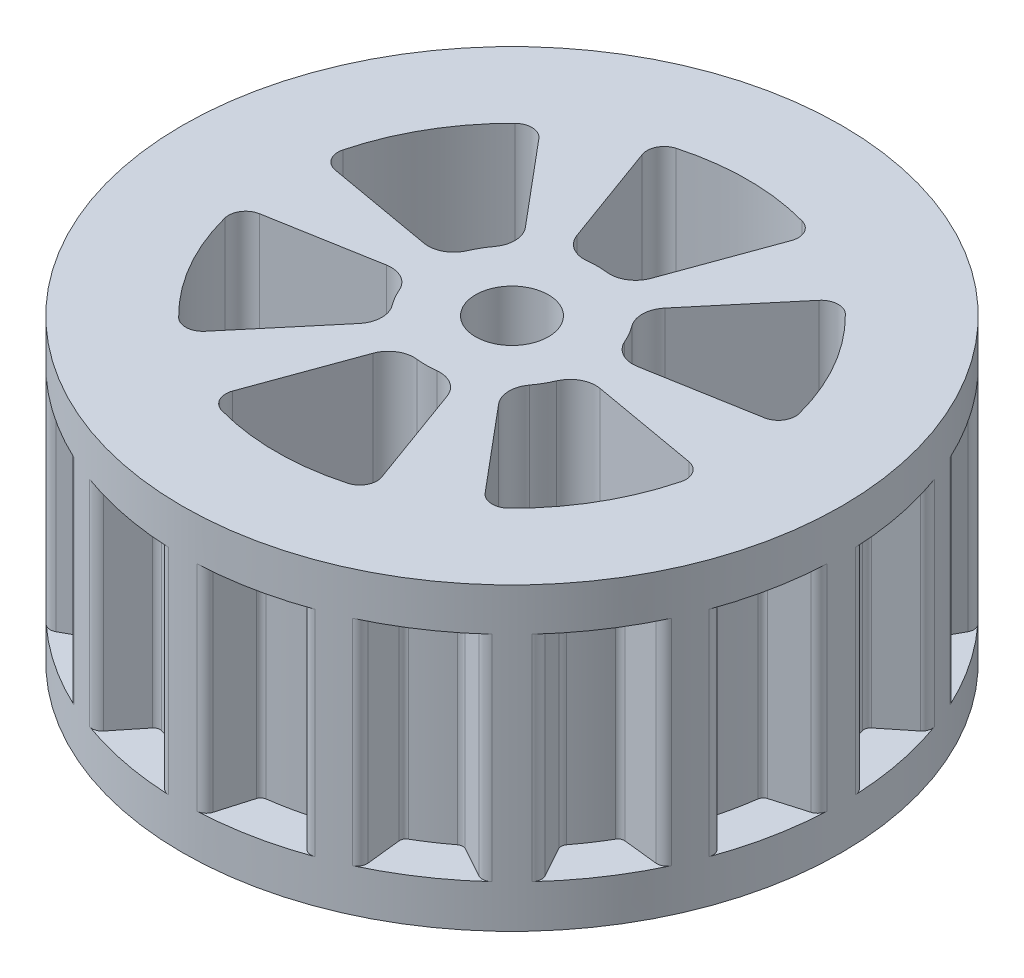
SolidWorks part; units mm, degrees
ref_plane "前视基准面" through (0, 0, 0) normal (0, 0, 1) x (1, 0, 0)
ref_plane "上视基准面" through (0, 0, 0) normal (0, 1, 0) x (1, 0, 0)
ref_plane "右视基准面" through (0, 0, 0) normal (1, 0, 0) x (0, 0, -1)
sketch "草图1" plane through (0, 0, 0) normal (0, 1, 0) x (1, 0, 0)
  circle A0 centre (0, 0) radius 76.925
extrude "凸台-拉伸1" add sketch "草图1" along normal blind 10
ref_plane "基准面1" through (0, 10, 0) normal (0, 1, 0) x (1, 0, 0)
sketch "草图2" plane through (0, 10, 0) normal (0, 1, 0) x (1, 0, 0)
  line L0 (0, 47.7566) -> (0, -19.898) construction
  line L1 (-34.7968, 0) -> (37.1562, 0) construction
  line L2 (0, 0) -> (6.2332, 95.8691) construction
  line L3 (4.9909, 76.7629) -> (8.95, 63.2066) construction
  line L4 (0, 0) -> (18.3427, 92.2148) construction
  line L5 (5.4476, 75.1994) -> (7.729, 67.3874)
  line L6 (-5.4476, 75.1994) -> (-7.729, 67.3874)
  line L7 (23.7447, 71.5599) -> (18.6474, 65.2156)
  line L8 (33.8105, 67.3905) -> (32.9287, 59.3001)
  line L9 (49.322, 57.026) -> (42.1849, 53.1153)
  line L10 (57.026, 49.322) -> (53.1153, 42.1849)
  line L11 (67.3905, 33.8105) -> (59.3001, 32.9287)
  line L12 (71.5599, 23.7447) -> (65.2156, 18.6474)
  line L13 (75.1994, 5.4476) -> (67.3874, 7.729)
  line L14 (75.1994, -5.4476) -> (67.3874, -7.729)
  line L15 (71.5599, -23.7447) -> (65.2156, -18.6474)
  line L16 (67.3905, -33.8105) -> (59.3001, -32.9287)
  line L17 (57.026, -49.322) -> (53.1153, -42.1849)
  line L18 (49.322, -57.026) -> (42.1849, -53.1153)
  line L19 (33.8105, -67.3905) -> (32.9287, -59.3001)
  line L20 (23.7447, -71.5599) -> (18.6474, -65.2156)
  line L21 (5.4476, -75.1994) -> (7.729, -67.3874)
  line L22 (-5.4476, -75.1994) -> (-7.729, -67.3874)
  line L23 (-23.7447, -71.5599) -> (-18.6474, -65.2156)
  line L24 (-33.8105, -67.3905) -> (-32.9287, -59.3001)
  line L25 (-49.322, -57.026) -> (-42.1849, -53.1153)
  line L26 (-57.026, -49.322) -> (-53.1153, -42.1849)
  line L27 (-67.3905, -33.8105) -> (-59.3001, -32.9287)
  line L28 (-71.5599, -23.7447) -> (-65.2156, -18.6474)
  line L29 (-75.1994, -5.4476) -> (-67.3874, -7.729)
  line L30 (-75.1994, 5.4476) -> (-67.3874, 7.729)
  line L31 (-71.5599, 23.7447) -> (-65.2156, 18.6474)
  line L32 (-67.3905, 33.8105) -> (-59.3001, 32.9287)
  line L33 (-57.026, 49.322) -> (-53.1153, 42.1849)
  line L34 (-49.322, 57.026) -> (-42.1849, 53.1153)
  line L35 (-33.8105, 67.3905) -> (-32.9287, 59.3001)
  line L36 (-23.7447, 71.5599) -> (-18.6474, 65.2156)
  arc A0 (3.3396, 76.8525) -> (-3.3396, 76.8525) centre (0, 0) ccw
  arc A1 (17.0949, 64.7049) -> (18.6474, 65.2156) centre (17.4781, 66.1551) ccw
  arc A2 (23.7447, 71.5599) -> (26.3248, 72.2804) centre (25.5377, 70.1193) cw
  arc A3 (17.0949, 64.7049) -> (8.9678, 66.3214) centre (0, 0) ccw
  arc A4 (5.4476, 75.1994) -> (3.3396, 76.8525) centre (3.2398, 74.5546) ccw
  arc A5 (8.9678, 66.3214) -> (7.729, 67.3874) centre (9.1688, 67.8079) cw
  arc A6 (32.4956, 69.7244) -> (26.3248, 72.2804) centre (0, 0) ccw
  arc A7 (-8.9678, 66.3214) -> (-7.729, 67.3874) centre (-9.1688, 67.8079) ccw
  arc A8 (-5.4476, 75.1994) -> (-3.3396, 76.8525) centre (-3.2398, 74.5546) cw
  arc A9 (33.8105, 67.3905) -> (32.4956, 69.7244) centre (31.524, 67.6397) ccw
  arc A10 (33.6653, 57.8412) -> (32.9287, 59.3001) centre (34.4199, 59.1376) cw
  arc A11 (40.5551, 53.2376) -> (33.6653, 57.8412) centre (0, 0) ccw
  arc A12 (40.5551, 53.2376) -> (42.1849, 53.1153) centre (41.4641, 54.4308) ccw
  arc A13 (49.322, 57.026) -> (51.9814, 56.7044) centre (50.4272, 55.009) cw
  arc A14 (56.7044, 51.9814) -> (51.9814, 56.7044) centre (0, 0) ccw
  arc A15 (57.026, 49.322) -> (56.7044, 51.9814) centre (55.009, 50.4272) ccw
  arc A16 (53.2376, 40.5551) -> (53.1153, 42.1849) centre (54.4308, 41.4641) cw
  arc A17 (57.8412, 33.6653) -> (53.2376, 40.5551) centre (0, 0) ccw
  arc A18 (57.8412, 33.6653) -> (59.3001, 32.9287) centre (59.1376, 34.4199) ccw
  arc A19 (67.3905, 33.8105) -> (69.7244, 32.4956) centre (67.6397, 31.524) cw
  arc A20 (72.2804, 26.3248) -> (69.7244, 32.4956) centre (0, 0) ccw
  arc A21 (71.5599, 23.7447) -> (72.2804, 26.3248) centre (70.1193, 25.5377) ccw
  arc A22 (64.7049, 17.0949) -> (65.2156, 18.6474) centre (66.1551, 17.4781) cw
  arc A23 (66.3214, 8.9678) -> (64.7049, 17.0949) centre (0, 0) ccw
  arc A24 (66.3214, 8.9678) -> (67.3874, 7.729) centre (67.8079, 9.1688) ccw
  arc A25 (75.1994, 5.4476) -> (76.8525, 3.3396) centre (74.5546, 3.2398) cw
  arc A26 (76.8525, -3.3396) -> (76.8525, 3.3396) centre (0, 0) ccw
  arc A27 (75.1994, -5.4476) -> (76.8525, -3.3396) centre (74.5546, -3.2398) ccw
  arc A28 (66.3214, -8.9678) -> (67.3874, -7.729) centre (67.8079, -9.1688) cw
  arc A29 (64.7049, -17.0949) -> (66.3214, -8.9678) centre (0, 0) ccw
  arc A30 (64.7049, -17.0949) -> (65.2156, -18.6474) centre (66.1551, -17.4781) ccw
  arc A31 (71.5599, -23.7447) -> (72.2804, -26.3248) centre (70.1193, -25.5377) cw
  arc A32 (69.7244, -32.4956) -> (72.2804, -26.3248) centre (0, 0) ccw
  arc A33 (67.3905, -33.8105) -> (69.7244, -32.4956) centre (67.6397, -31.524) ccw
  arc A34 (57.8412, -33.6653) -> (59.3001, -32.9287) centre (59.1376, -34.4199) cw
  arc A35 (53.2376, -40.5551) -> (57.8412, -33.6653) centre (0, 0) ccw
  arc A36 (53.2376, -40.5551) -> (53.1153, -42.1849) centre (54.4308, -41.4641) ccw
  arc A37 (57.026, -49.322) -> (56.7044, -51.9814) centre (55.009, -50.4272) cw
  arc A38 (51.9814, -56.7044) -> (56.7044, -51.9814) centre (0, 0) ccw
  arc A39 (49.322, -57.026) -> (51.9814, -56.7044) centre (50.4272, -55.009) ccw
  arc A40 (40.5551, -53.2376) -> (42.1849, -53.1153) centre (41.4641, -54.4308) cw
  arc A41 (33.6653, -57.8412) -> (40.5551, -53.2376) centre (0, 0) ccw
  arc A42 (33.6653, -57.8412) -> (32.9287, -59.3001) centre (34.4199, -59.1376) ccw
  arc A43 (33.8105, -67.3905) -> (32.4956, -69.7244) centre (31.524, -67.6397) cw
  arc A44 (26.3248, -72.2804) -> (32.4956, -69.7244) centre (0, 0) ccw
  arc A45 (23.7447, -71.5599) -> (26.3248, -72.2804) centre (25.5377, -70.1193) ccw
  arc A46 (17.0949, -64.7049) -> (18.6474, -65.2156) centre (17.4781, -66.1551) cw
  arc A47 (8.9678, -66.3214) -> (17.0949, -64.7049) centre (0, 0) ccw
  arc A48 (8.9678, -66.3214) -> (7.729, -67.3874) centre (9.1688, -67.8079) ccw
  arc A49 (5.4476, -75.1994) -> (3.3396, -76.8525) centre (3.2398, -74.5546) cw
  arc A50 (-3.3396, -76.8525) -> (3.3396, -76.8525) centre (0, 0) ccw
  arc A51 (-5.4476, -75.1994) -> (-3.3396, -76.8525) centre (-3.2398, -74.5546) ccw
  arc A52 (-8.9678, -66.3214) -> (-7.729, -67.3874) centre (-9.1688, -67.8079) cw
  arc A53 (-17.0949, -64.7049) -> (-8.9678, -66.3214) centre (0, 0) ccw
  arc A54 (-17.0949, -64.7049) -> (-18.6474, -65.2156) centre (-17.4781, -66.1551) ccw
  arc A55 (-23.7447, -71.5599) -> (-26.3248, -72.2804) centre (-25.5377, -70.1193) cw
  arc A56 (-32.4956, -69.7244) -> (-26.3248, -72.2804) centre (0, 0) ccw
  arc A57 (-33.8105, -67.3905) -> (-32.4956, -69.7244) centre (-31.524, -67.6397) ccw
  arc A58 (-33.6653, -57.8412) -> (-32.9287, -59.3001) centre (-34.4199, -59.1376) cw
  arc A59 (-40.5551, -53.2376) -> (-33.6653, -57.8412) centre (0, 0) ccw
  arc A60 (-40.5551, -53.2376) -> (-42.1849, -53.1153) centre (-41.4641, -54.4308) ccw
  arc A61 (-49.322, -57.026) -> (-51.9814, -56.7044) centre (-50.4272, -55.009) cw
  arc A62 (-56.7044, -51.9814) -> (-51.9814, -56.7044) centre (0, 0) ccw
  arc A63 (-57.026, -49.322) -> (-56.7044, -51.9814) centre (-55.009, -50.4272) ccw
  arc A64 (-53.2376, -40.5551) -> (-53.1153, -42.1849) centre (-54.4308, -41.4641) cw
  arc A65 (-57.8412, -33.6653) -> (-53.2376, -40.5551) centre (0, 0) ccw
  arc A66 (-57.8412, -33.6653) -> (-59.3001, -32.9287) centre (-59.1376, -34.4199) ccw
  arc A67 (-67.3905, -33.8105) -> (-69.7244, -32.4956) centre (-67.6397, -31.524) cw
  arc A68 (-72.2804, -26.3248) -> (-69.7244, -32.4956) centre (0, 0) ccw
  arc A69 (-71.5599, -23.7447) -> (-72.2804, -26.3248) centre (-70.1193, -25.5377) ccw
  arc A70 (-64.7049, -17.0949) -> (-65.2156, -18.6474) centre (-66.1551, -17.4781) cw
  arc A71 (-66.3214, -8.9678) -> (-64.7049, -17.0949) centre (0, 0) ccw
  arc A72 (-66.3214, -8.9678) -> (-67.3874, -7.729) centre (-67.8079, -9.1688) ccw
  arc A73 (-75.1994, -5.4476) -> (-76.8525, -3.3396) centre (-74.5546, -3.2398) cw
  arc A74 (-76.8525, 3.3396) -> (-76.8525, -3.3396) centre (0, 0) ccw
  arc A75 (-75.1994, 5.4476) -> (-76.8525, 3.3396) centre (-74.5546, 3.2398) ccw
  arc A76 (-66.3214, 8.9678) -> (-67.3874, 7.729) centre (-67.8079, 9.1688) cw
  arc A77 (-64.7049, 17.0949) -> (-66.3214, 8.9678) centre (0, 0) ccw
  arc A78 (-64.7049, 17.0949) -> (-65.2156, 18.6474) centre (-66.1551, 17.4781) ccw
  arc A79 (-71.5599, 23.7447) -> (-72.2804, 26.3248) centre (-70.1193, 25.5377) cw
  arc A80 (-69.7244, 32.4956) -> (-72.2804, 26.3248) centre (0, 0) ccw
  arc A81 (-67.3905, 33.8105) -> (-69.7244, 32.4956) centre (-67.6397, 31.524) ccw
  arc A82 (-57.8412, 33.6653) -> (-59.3001, 32.9287) centre (-59.1376, 34.4199) cw
  arc A83 (-53.2376, 40.5551) -> (-57.8412, 33.6653) centre (0, 0) ccw
  arc A84 (-53.2376, 40.5551) -> (-53.1153, 42.1849) centre (-54.4308, 41.4641) ccw
  arc A85 (-57.026, 49.322) -> (-56.7044, 51.9814) centre (-55.009, 50.4272) cw
  arc A86 (-51.9814, 56.7044) -> (-56.7044, 51.9814) centre (0, 0) ccw
  arc A87 (-49.322, 57.026) -> (-51.9814, 56.7044) centre (-50.4272, 55.009) ccw
  arc A88 (-40.5551, 53.2376) -> (-42.1849, 53.1153) centre (-41.4641, 54.4308) cw
  arc A89 (-33.6653, 57.8412) -> (-40.5551, 53.2376) centre (0, 0) ccw
  arc A90 (-33.6653, 57.8412) -> (-32.9287, 59.3001) centre (-34.4199, 59.1376) ccw
  arc A91 (-33.8105, 67.3905) -> (-32.4956, 69.7244) centre (-31.524, 67.6397) cw
  arc A92 (-26.3248, 72.2804) -> (-32.4956, 69.7244) centre (0, 0) ccw
  arc A93 (-23.7447, 71.5599) -> (-26.3248, 72.2804) centre (-25.5377, 70.1193) ccw
  arc A94 (-17.0949, 64.7049) -> (-18.6474, 65.2156) centre (-17.4781, 66.1551) cw
  arc A95 (-8.9678, 66.3214) -> (-17.0949, 64.7049) centre (0, 0) ccw
  point P6 (4.9909, 76.7629)
  point P12 (8.0043, 66.4446)
  point P18 (0, 76.925)
  point P27 (8.0043, 66.4446)
  point P224 (0, 0)
  dimension "D1" = 3.72
  dimension "D4" = 2.3
  dimension "D5" = 1.5
  dimension "D2" = 20
  dimension "D6" = 16
extrude "凸台-拉伸2" add sketch "草图2" along normal blind 50
ref_plane "基准面2" through (0, 60, 0) normal (0, 1, 0) x (1, 0, 0)
sketch "草图3" plane through (0, 60, 0) normal (0, 1, 0) x (1, 0, 0)
  circle A0 centre (0, 0) radius 76.925
extrude "凸台-拉伸3" add sketch "草图3" along normal blind 10
sketch "草图13" plane through (0, 0, 0) normal (0, 1, 0) x (1, 0, 0)
  line L0 (-34.0547, 0) -> (52.5908, 0) construction
  line L1 (0, 44.6691) -> (0, -25.8112) construction
  line L2 (0, 0) -> (2.9072, 7.9874) construction
  line L3 (17.3893, 47.7767) -> (8.6525, 23.7726)
  line L4 (8.6525, 23.7726) -> (20.35, 55.9112) construction
  line L5 (-17.3893, 47.7767) -> (-8.6525, 23.7726)
  line L6 (32.6812, 38.9479) -> (16.2614, 19.3796)
  line L7 (50.0705, 8.8288) -> (24.9139, 4.393)
  line L8 (50.0705, -8.8288) -> (24.9139, -4.393)
  line L9 (32.6812, -38.9479) -> (16.2614, -19.3796)
  line L10 (17.3893, -47.7767) -> (8.6525, -23.7726)
  line L11 (-17.3893, -47.7767) -> (-8.6525, -23.7726)
  line L12 (-32.6812, -38.9479) -> (-16.2614, -19.3796)
  line L13 (-50.0705, -8.8288) -> (-24.9139, -4.393)
  line L14 (-50.0705, 8.8288) -> (-24.9139, 4.393)
  line L15 (-32.6812, 38.9479) -> (-16.2614, 19.3796)
  circle A0 centre (0, 0) radius 8.5
  arc A1 (2.3187, 19.8651) -> (-2.3187, 19.8651) centre (0, 0) ccw
  arc A2 (14.6996, 52.9993) -> (-14.6996, 52.9993) centre (0, 0) ccw
  arc A3 (17.3893, 47.7767) -> (14.6996, 52.9993) centre (13.6305, 49.1448) ccw
  arc A4 (8.6525, 23.7726) -> (2.3187, 19.8651) centre (3.0143, 25.8247) cw
  arc A5 (-8.6525, 23.7726) -> (-2.3187, 19.8651) centre (-3.0143, 25.8247) ccw
  arc A6 (-17.3893, 47.7767) -> (-14.6996, 52.9993) centre (-13.6305, 49.1448) cw
  arc A7 (53.2485, 13.7694) -> (38.5489, 39.2298) centre (0, 0) ccw
  arc A8 (32.6812, 38.9479) -> (38.5489, 39.2298) centre (35.7454, 36.3768) cw
  arc A9 (16.2614, 19.3796) -> (16.0443, 11.9406) centre (20.8576, 15.5228) ccw
  arc A10 (18.3631, 7.9245) -> (16.0443, 11.9406) centre (0, 0) ccw
  arc A11 (24.9139, 4.393) -> (18.3631, 7.9245) centre (23.872, 10.3018) cw
  arc A12 (50.0705, 8.8288) -> (53.2485, 13.7694) centre (49.3759, 12.768) ccw
  arc A13 (38.5489, -39.2298) -> (53.2485, -13.7694) centre (0, 0) ccw
  arc A14 (50.0705, -8.8288) -> (53.2485, -13.7694) centre (49.3759, -12.768) cw
  arc A15 (24.9139, -4.393) -> (18.3631, -7.9245) centre (23.872, -10.3018) ccw
  arc A16 (16.0443, -11.9406) -> (18.3631, -7.9245) centre (0, 0) ccw
  arc A17 (16.2614, -19.3796) -> (16.0443, -11.9406) centre (20.8576, -15.5228) cw
  arc A18 (32.6812, -38.9479) -> (38.5489, -39.2298) centre (35.7454, -36.3768) ccw
  arc A19 (-14.6996, -52.9993) -> (14.6996, -52.9993) centre (0, 0) ccw
  arc A20 (17.3893, -47.7767) -> (14.6996, -52.9993) centre (13.6305, -49.1448) cw
  arc A21 (8.6525, -23.7726) -> (2.3187, -19.8651) centre (3.0143, -25.8247) ccw
  arc A22 (-2.3187, -19.8651) -> (2.3187, -19.8651) centre (0, 0) ccw
  arc A23 (-8.6525, -23.7726) -> (-2.3187, -19.8651) centre (-3.0143, -25.8247) cw
  arc A24 (-17.3893, -47.7767) -> (-14.6996, -52.9993) centre (-13.6305, -49.1448) ccw
  arc A25 (-53.2485, -13.7694) -> (-38.5489, -39.2298) centre (0, 0) ccw
  arc A26 (-32.6812, -38.9479) -> (-38.5489, -39.2298) centre (-35.7454, -36.3768) cw
  arc A27 (-16.2614, -19.3796) -> (-16.0443, -11.9406) centre (-20.8576, -15.5228) ccw
  arc A28 (-18.3631, -7.9245) -> (-16.0443, -11.9406) centre (0, 0) ccw
  arc A29 (-24.9139, -4.393) -> (-18.3631, -7.9245) centre (-23.872, -10.3018) cw
  arc A30 (-50.0705, -8.8288) -> (-53.2485, -13.7694) centre (-49.3759, -12.768) ccw
  arc A31 (-38.5489, 39.2298) -> (-53.2485, 13.7694) centre (0, 0) ccw
  arc A32 (-50.0705, 8.8288) -> (-53.2485, 13.7694) centre (-49.3759, 12.768) cw
  arc A33 (-24.9139, 4.393) -> (-18.3631, 7.9245) centre (-23.872, 10.3018) ccw
  arc A34 (-16.0443, 11.9406) -> (-18.3631, 7.9245) centre (0, 0) ccw
  arc A35 (-16.2614, 19.3796) -> (-16.0443, 11.9406) centre (-20.8576, 15.5228) cw
  arc A36 (-32.6812, 38.9479) -> (-38.5489, 39.2298) centre (-35.7454, 36.3768) ccw
  point P9 (18.8111, 51.6831)
  point P11 (6.8404, 18.7939)
  point P15 (18.8111, 51.6831)
  point P19 (6.8404, 18.7939)
  point P88 (0, 0)
  dimension "D1" = 20
  dimension "D2" = 4
  dimension "D3" = 6
extrude "切除-拉伸5" cut sketch "草图13" along normal through all
